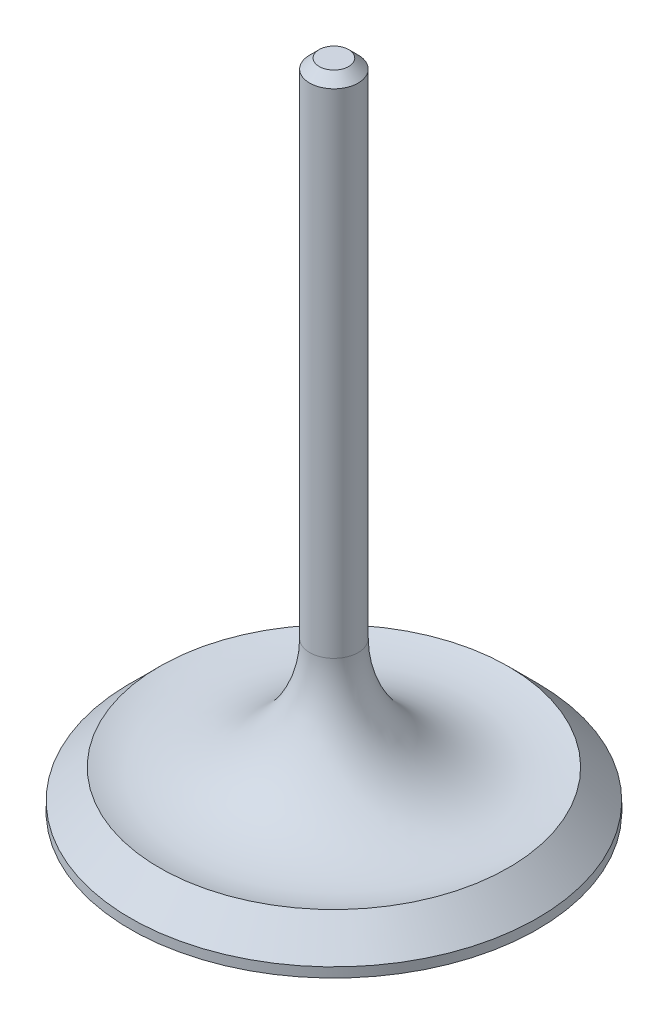
SolidWorks part; units mm, degrees
ref_plane "Front Plane" through (0, 0, 0) normal (0, 0, 1) x (1, 0, 0)
ref_plane "Top Plane" through (0, 0, 0) normal (0, 1, 0) x (1, 0, 0)
ref_plane "Right Plane" through (0, 0, 0) normal (1, 0, 0) x (0, 0, -1)
sketch "Sketch2" plane through (0, 0, 0) normal (1, 0, 0) x (0, 0, -1)
  line L0 (0, 0) -> (0, 85.55)
  line L1 (0, 85.55) -> (3.18, 85.55)
  line L2 (3.18, 85.55) -> (3.18, 19.6724)
  line L3 (22.86, 5.08) -> (26.67, 1.27)
  line L4 (26.67, 1.27) -> (26.67, 0)
  line L5 (26.67, 0) -> (0, 0)
  arc A0 (3.18, 19.6724) -> (22.86, 5.08) centre (18.43, 19.6724) ccw
  dimension "D7" = 15.25
  dimension "D1" = 85.55
  dimension "D2" = 26.67
  dimension "D3" = 1.27
  dimension "D4" = 3.81
  dimension "D5" = 45
  dimension "D6" = 3.18
revolve "Revolve1" add sketch "Sketch2" angle 360 about L0
chamfer "Chamfer1" distance 1.25 angle 45 1 edges at (0, 85.55, -3.18)
